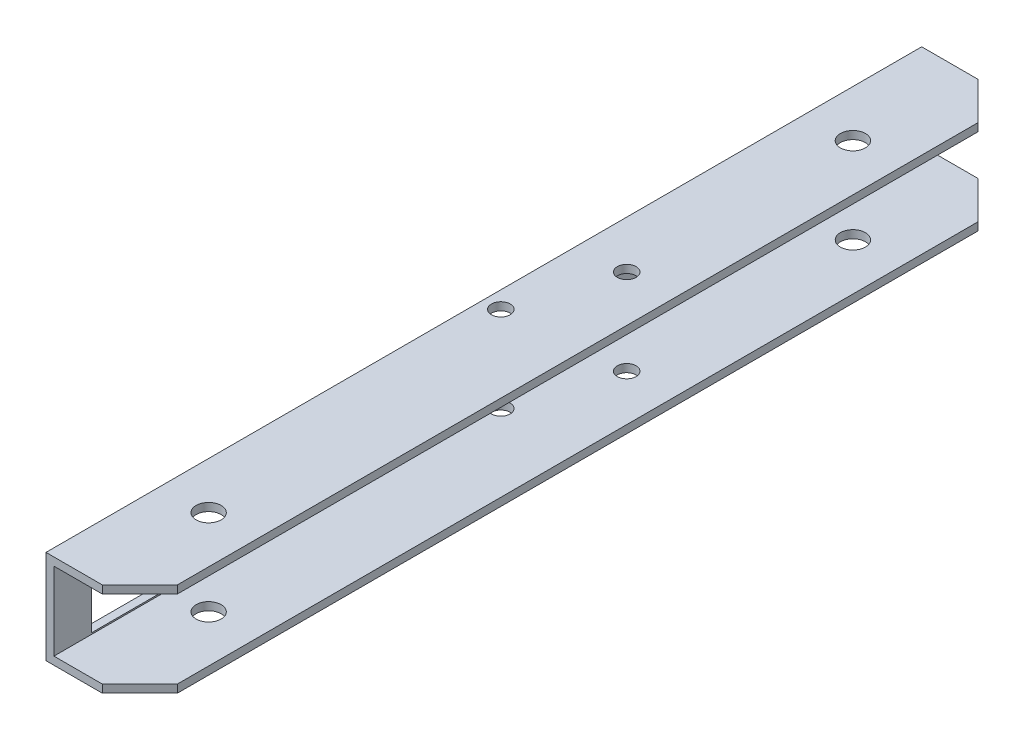
SolidWorks part; units mm, degrees
ref_plane "Front Plane" through (0, 0, 0) normal (0, 0, 1) x (1, 0, 0)
ref_plane "Top Plane" through (0, 0, 0) normal (0, 1, 0) x (1, 0, 0)
ref_plane "Right Plane" through (0, 0, 0) normal (1, 0, 0) x (0, 0, -1)
sketch "Sketch1" plane through (0, 0, 0) normal (0, 0, 1) x (1, 0, 0)
  line L0 (0, -37.5) -> (0, 37.5)
  line L1 (0, 37.5) -> (75, 37.5)
  line L2 (75, 37.5) -> (75, 31.15)
  line L3 (75, 31.15) -> (6.35, 31.15)
  line L4 (6.35, 31.15) -> (6.35, -31.15)
  line L5 (6.35, -31.15) -> (75, -31.15)
  line L6 (75, -31.15) -> (75, -37.5)
  line L7 (75, -37.5) -> (0, -37.5)
  line L8 (0, 0) -> (6.35, 0) construction
  dimension "D1" = 75
  dimension "D2" = 75
  dimension "D3" = 6.35
extrude "Boss-Extrude1" add sketch "Sketch1" along normal blind 700
sketch "Sketch3" plane through (0, 0, 0) normal (-1, 0, 0) x (0, 0, 1)
  line L0 (30, -30) -> (155, -30)
  line L1 (30, -30) -> (30, 30)
  line L2 (155, -30) -> (155, 30)
  line L3 (30, 30) -> (155, 30)
  line L4 (30, -30) -> (155, 30) construction
  line L5 (155, -30) -> (30, 30) construction
  line L6 (350, -37.5) -> (350, 96.3047) construction
  line L7 (700, -37.5) -> (0, -37.5) construction
  line L8 (0, 0) -> (92.5, 0) construction
  line L9 (670, -30) -> (545, -30)
  line L10 (545, -30) -> (545, 30)
  line L11 (670, 30) -> (545, 30)
  line L12 (670, -30) -> (670, 30)
  line L13 (700, 37.5) -> (700, -37.5) construction
  line L14 (400, 10.3833) -> (373, 10.3833)
  line L15 (400, 10.3833) -> (400, -10.3833)
  line L16 (300, 10.3833) -> (300, -10.3833) construction
  line L17 (400, -10.3833) -> (393, -10.3833)
  line L18 (400, 10.3833) -> (300, -10.3833) construction
  line L19 (300, 10.3833) -> (400, -10.3833) construction
  line L20 (307, 10.3833) -> (300, 10.3833)
  line L21 (373, -10.3833) -> (373, -31.15) construction
  line L22 (373, -31.15) -> (327, -31.15)
  line L23 (327, -31.15) -> (327, -10.3833)
  line L24 (373, 31.15) -> (327, 31.15)
  line L25 (373, 31.15) -> (373, 10.3833)
  line L26 (327, 31.15) -> (327, 10.3833) construction
  line L27 (700, -31.15) -> (0, -31.15) construction
  line L28 (373, 31.15) -> (327, 10.3833) construction
  line L29 (327, 31.15) -> (373, 10.3833) construction
  line L30 (327, 31.15) -> (307, 31.15)
  line L31 (327, -10.3833) -> (300, -10.3833)
  line L32 (300, 10.3833) -> (270, 10.3833)
  line L33 (270, 10.3833) -> (270, -10.3833)
  line L34 (270, -10.3833) -> (300, -10.3833)
  line L35 (700, 31.15) -> (0, 31.15) construction
  line L36 (307, 31.15) -> (307, 10.3833)
  line L37 (373, -31.15) -> (393, -31.15)
  line L38 (393, -31.15) -> (393, -10.3833)
  point P1 (92.5, 0)
  point P19 (350, 0)
  point P28 (350, 20.7667)
  dimension "D1" = 60
  dimension "D2" = 30
  dimension "D3" = 125
  dimension "D4" = 20
  dimension "D5" = 100
  dimension "D6" = 46
  dimension "D9" = 30
extrude "Cut-Extrude1" cut sketch "Sketch3" against normal through all
chamfer "Chamfer1" distance 30 angle 45 4 edges at (75, 34.325, 700) (75, -34.325, 700) (75, -34.325, 0) (75, 34.325, 0)
sketch "Sketch4" plane through (0, 37.5, 0) normal (0, 1, 0) x (1, 0, 0)
  line L0 (75, -607.5) -> (37.5, -607.5) construction
  line L1 (75, -670) -> (75, -30) construction
  line L2 (0, -670) -> (0, -545) construction
  line L4 (0, -545.4516) -> (0, -669.5484) construction
  line L5 (0, -700) -> (0, 0) construction
  line L6 (0, -607.5) -> (37.5, -607.5) construction
  line L7 (0, -350) -> (49.4239, -350) construction
  circle A0 centre (37.5, -607.5) radius 10
  circle A1 centre (37.5, -607.5) radius 62.5 construction
  circle A2 centre (37.5, -607.5) radius 72.5 construction
  circle A3 centre (37.5, -92.5) radius 10
  dimension "D1" = 20
  dimension "D2" = 125
  dimension "D3" = 145
  dimension "D4" = 124.0967
extrude "Cut-Extrude2" cut sketch "Sketch4" against normal through all
sketch "Sketch5" plane through (0, -37.5, 0) normal (0, -1, 0) x (1, 0, 0)
  line L1 (0, 350) -> (13.565, 350) construction
  line L6 (75, 670) -> (75, 30) construction
  line L7 (37.5, 607.5) -> (13.565, 350) construction
  line L8 (13.565, 350) -> (37.5, 92.5) construction
  line L11 (0, 700) -> (0, 0) construction
  circle A0 centre (38, 273.823) radius 7.5
  circle A2 centre (13.565, 350) radius 7.5
  point P10 (37.5, 92.5)
  point P11 (37.5, 607.5)
  dimension "D1" = 15
  dimension "D2" = 37
  dimension "D3" = 80
  dimension "D4" = 13.565
  dimension "D5" = 258.61
extrude "Cut-Extrude3" cut sketch "Sketch5" against normal through all
chamfer "Chamfer2" distance 3 angle 45 5 edges at (0, -20.7667, 393) (0, 20.7667, 307) (6.35, 0, 270) (6.35, 20.7667, 373) (6.35, -20.7667, 327)
fillet "Fillet1" radius 3 8 edges at (1.675, 31.15, 373) (3.175, 10.3833, 400) (3.175, -10.3833, 400) (1.675, -31.15, 327) (1.675, -10.3833, 270) (1.675, 10.3833, 270) (4.675, -31.15, 393) (4.675, 31.15, 307)
